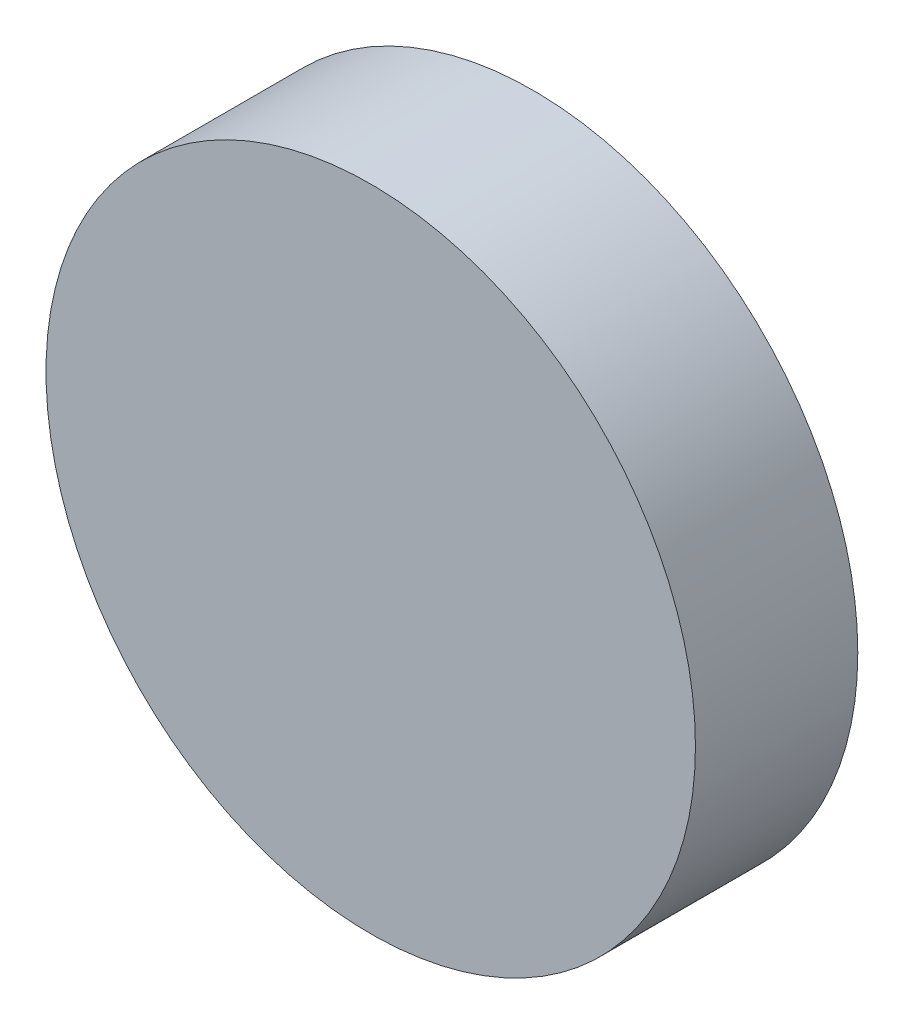
SolidWorks part; units mm, degrees
ref_plane "Front Plane" through (0, 0, 0) normal (0, 0, 1) x (1, 0, 0)
ref_plane "Top Plane" through (0, 0, 0) normal (0, 1, 0) x (1, 0, 0)
ref_plane "Right Plane" through (0, 0, 0) normal (1, 0, 0) x (0, 0, -1)
sketch "Sketch1" plane through (0, 0, 0) normal (0, 0, 1) x (1, 0, 0)
  circle A0 centre (66.5, -2.4373) radius 30
  dimension "D1" = 60
extrude "Boss-Extrude1" add sketch "Sketch1" along normal blind 15
